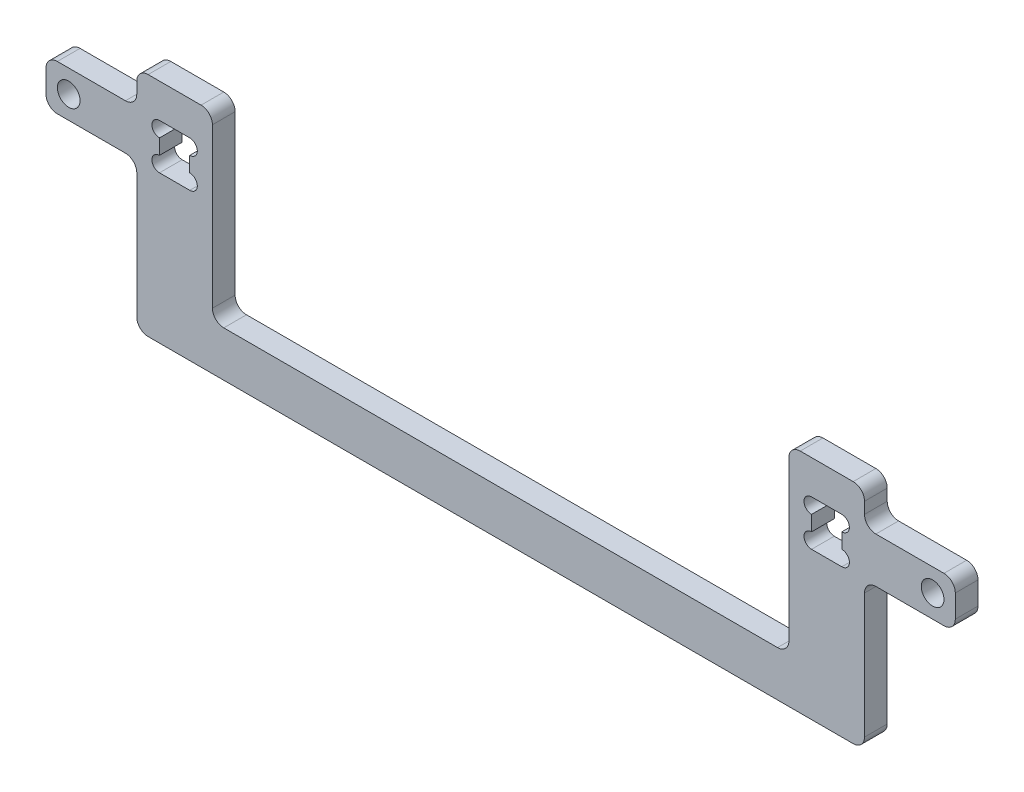
SolidWorks part; units mm, degrees
ref_plane "前视基准面" through (0, 0, 0) normal (0, 0, 1) x (1, 0, 0)
ref_plane "上视基准面" through (0, 0, 0) normal (0, 1, 0) x (1, 0, 0)
ref_plane "右视基准面" through (0, 0, 0) normal (1, 0, 0) x (0, 0, -1)
sketch "草图1" plane through (0, 0, 0) normal (0, 0, 1) x (1, 0, 0)
  line L0 (18, 0) -> (18, -24)
  line L1 (0, 0) -> (18, 0)
  line L2 (0, 0) -> (0, -30)
  line L3 (0, -30) -> (96.2, -30)
  line L4 (96.2, 0) -> (96.2, -30)
  line L5 (18, -24) -> (78.2, -24)
  line L6 (78.2, -24) -> (78.2, 0)
  line L7 (78.2, 0) -> (96.2, 0)
  line L8 (48.1, -24) -> (48.1, -20) construction
  line L9 (3, -4.5) -> (7, -4.5)
  line L10 (3, -6.5) -> (3, -8.5)
  line L11 (3, -10.5) -> (7, -10.5)
  line L12 (7, -6.5) -> (7, -8.5)
  line L17 (89.2, -6.5) -> (89.2, -8.5)
  line L18 (93.2, -10.5) -> (89.2, -10.5)
  line L19 (93.2, -6.5) -> (93.2, -8.5)
  line L20 (93.2, -4.5) -> (89.2, -4.5)
  arc A0 (3, -4.5) -> (3, -6.5) centre (3, -5.5) ccw
  arc A1 (7, -6.5) -> (7, -4.5) centre (7, -5.5) ccw
  arc A2 (3, -8.5) -> (3, -10.5) centre (3, -9.5) ccw
  arc A3 (7, -10.5) -> (7, -8.5) centre (7, -9.5) ccw
  arc A4 (89.2, -10.5) -> (89.2, -8.5) centre (89.2, -9.5) cw
  arc A5 (93.2, -8.5) -> (93.2, -10.5) centre (93.2, -9.5) cw
  arc A6 (89.2, -6.5) -> (89.2, -4.5) centre (89.2, -5.5) cw
  arc A7 (93.2, -4.5) -> (93.2, -6.5) centre (93.2, -5.5) cw
  dimension "D10" = 2
  dimension "D1" = 30
  dimension "D2" = 96.2
  dimension "D3" = 18
  dimension "D4" = 18
  dimension "D5" = 6
  dimension "D6" = 6
  dimension "D7" = 4
  dimension "D8" = 3
  dimension "D9" = 4.5
extrude "凸台-拉伸1" add sketch "草图1" along normal blind 3
sketch "草图2" plane through (0, 0, 3) normal (0, 0, 1) x (1, 0, 0)
  line L0 (18, 0) -> (0, 0) construction
  line L1 (10, 0) -> (18, 0)
  line L2 (10, 0) -> (10, -4.5)
  line L3 (10, -4.5) -> (18, -4.5)
  line L4 (18, 0) -> (18, -4.5)
  line L5 (18, -24) -> (18, 0) construction
  line L6 (7, -4.5) -> (3, -4.5) construction
  line L7 (7, -8.5) -> (7, -6.5) construction
  line L8 (3, -10.5) -> (7, -10.5) construction
  line L9 (18, -24) -> (10, -24)
  line L10 (18, -24) -> (18, -10.5)
  line L11 (18, -10.5) -> (10, -10.5)
  line L12 (10, -24) -> (10, -10.5)
  line L13 (48.1, -24) -> (48.1, -30) construction
  line L14 (78.2, -24) -> (18, -24) construction
  line L15 (0, -30) -> (96.2, -30) construction
  line L16 (86.2, -24) -> (86.2, -10.5)
  line L17 (78.2, -10.5) -> (86.2, -10.5)
  line L18 (78.2, -24) -> (78.2, -10.5)
  line L19 (78.2, -24) -> (86.2, -24)
  line L20 (78.2, 0) -> (78.2, -4.5)
  line L21 (86.2, -4.5) -> (78.2, -4.5)
  line L22 (86.2, 0) -> (86.2, -4.5)
  line L23 (86.2, 0) -> (78.2, 0)
  dimension "D1" = 3
extrude "切除-拉伸1" cut sketch "草图2" against normal blind 3
sketch "草图4" plane through (0, 0, 3) normal (0, 0, 1) x (1, 0, 0)
  line L0 (10, -4.5) -> (18, -4.5) construction
  line L1 (10, -4.5) -> (86.2, -4.5)
  line L2 (10, -4.5) -> (10, -10.5)
  line L3 (10, -10.5) -> (86.2, -10.5)
  line L4 (86.2, -4.5) -> (86.2, -10.5)
  line L5 (86.2, -10.5) -> (78.2, -10.5) construction
  line L8 (86.2, -24) -> (86.2, -10.5) construction
  line L9 (10, -10.5) -> (10, -24) construction
extrude "切除-拉伸2" cut sketch "草图4" against normal blind 3
sketch "草图6" plane through (0, 0, 3) normal (0, 0, 1) x (1, 0, 0)
  line L0 (96.2, -4.5) -> (108.2, -4.5)
  line L1 (96.2, -30) -> (96.2, 0) construction
  line L2 (108.2, -4.5) -> (108.2, -10.5)
  line L3 (108.2, -10.5) -> (96.2, -10.5)
  line L5 (96.2, -4.5) -> (96.2, -10.5)
  line L6 (48.1, -24) -> (48.1, -30) construction
  line L7 (86.2, -24) -> (10, -24) construction
  line L8 (0, -30) -> (96.2, -30) construction
  line L9 (0, -4.5) -> (0, -10.5)
  line L10 (-12, -10.5) -> (0, -10.5)
  line L11 (-12, -4.5) -> (-12, -10.5)
  line L12 (0, -4.5) -> (-12, -4.5)
  line L13 (93.2, -4.5) -> (89.2, -4.5) construction
  dimension "D1" = 12
  dimension "D2" = 6
extrude "凸台-拉伸2" add sketch "草图6" against normal blind 3
fillet "圆角1" radius 1.5 16 edges at (0, -30, 1.5) (96.2, -30, 1.5) (0, -10.5, 1.5) (-12, -10.5, 1.5) (-12, -4.5, 1.5) (0, -4.5, 1.5) (0, 0, 1.5) (10, 0, 1.5) (96.2, -10.5, 1.5) (108.2, -10.5, 1.5) (108.2, -4.5, 1.5) (96.2, -4.5, 1.5) (96.2, 0, 1.5) (86.2, 0, 1.5) (86.2, -24, 1.5) (10, -24, 1.5)
sketch "草图7" plane through (0, 0, 3) normal (0, 0, 1) x (1, 0, 0)
  line L0 (48.1, -21) -> (48.1, 49979) construction
  line L1 (84.7, -24) -> (11.5, -24) construction
  circle A0 centre (-9, -7.5) radius 1.5
  circle A1 centre (105.2, -7.5) radius 1.5
  point P7 (48.1, -24)
  dimension "D1" = 3
extrude "切除-拉伸3" cut sketch "草图7" against normal blind 10
